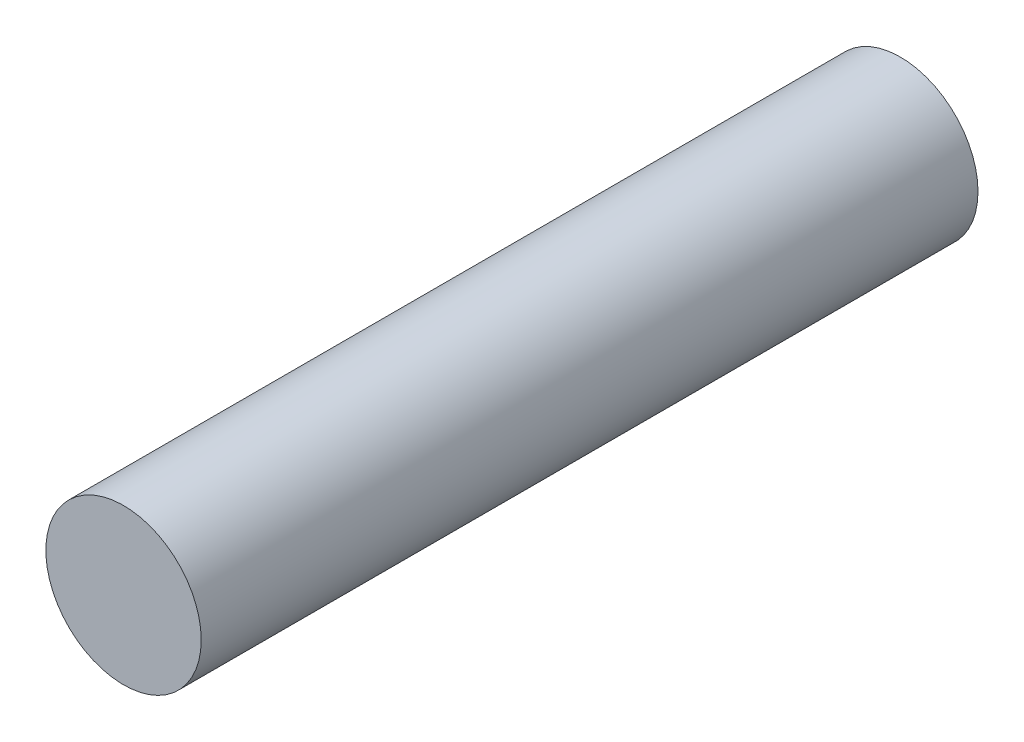
SolidWorks part; units mm, degrees
ref_plane "Front Plane" through (0, 0, 0) normal (0, 0, 1) x (1, 0, 0)
ref_plane "Top Plane" through (0, 0, 0) normal (0, 1, 0) x (1, 0, 0)
ref_plane "Right Plane" through (0, 0, 0) normal (1, 0, 0) x (0, 0, -1)
sketch "Sketch1" plane through (0, 0, 0) normal (0, 0, 1) x (1, 0, 0)
  circle A0 centre (0, 0) radius 1
  dimension "D1" = 2
extrude "Boss-Extrude1" add sketch "Sketch1" along normal mid plane 10
